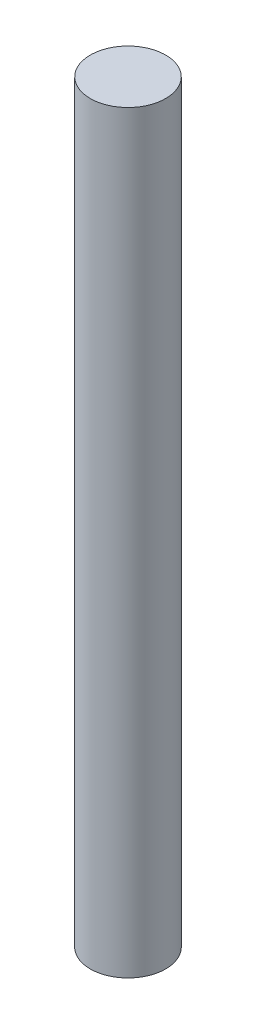
SolidWorks part; units mm, degrees
ref_plane "Front Plane" through (0, 0, 0) normal (0, 0, 1) x (1, 0, 0)
ref_plane "Top Plane" through (0, 0, 0) normal (0, 1, 0) x (1, 0, 0)
ref_plane "Right Plane" through (0, 0, 0) normal (1, 0, 0) x (0, 0, -1)
sketch "Sketch1" plane through (0, 0, 0) normal (0, 1, 0) x (1, 0, 0)
  circle A0 centre (0, 0) radius 12.7
  circle A1 centre (0, 0) radius 2
  dimension "D1" = 4
  dimension "D2" = 25.4
extrude "Boss-Extrude1" add sketch "Sketch1" along normal blind 254 contours A0 A1 | A1
